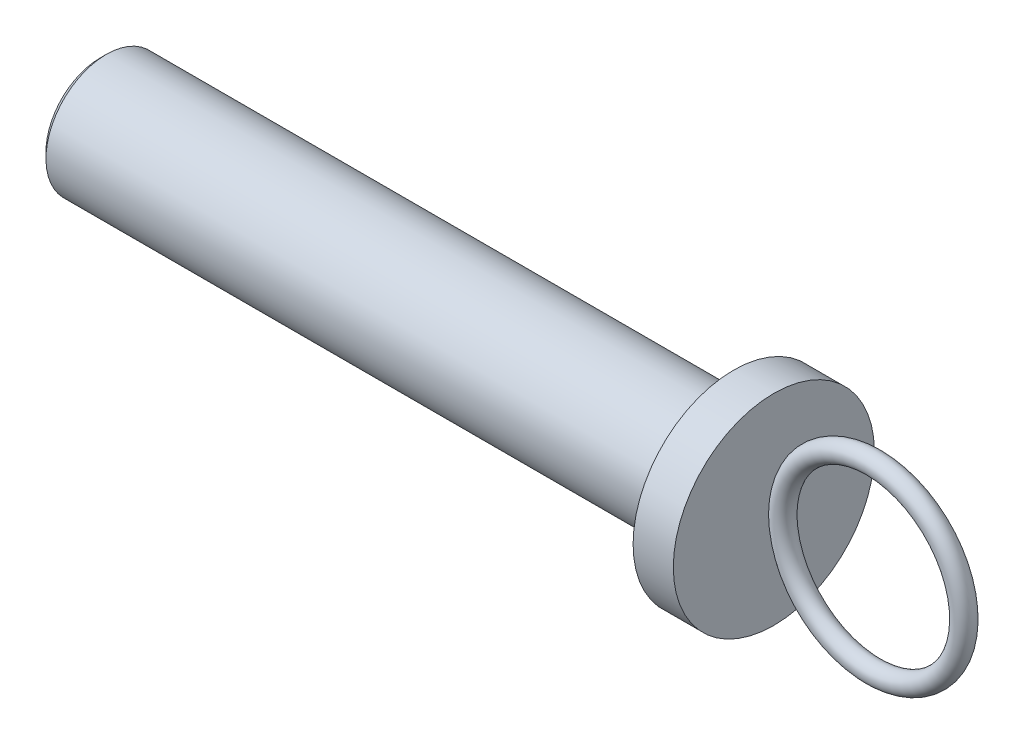
SolidWorks part; units mm, degrees
ref_plane "前视基准面" through (0, 0, 0) normal (0, 0, 1) x (1, 0, 0)
ref_plane "上视基准面" through (0, 0, 0) normal (0, 1, 0) x (1, 0, 0)
ref_plane "右视基准面" through (0, 0, 0) normal (1, 0, 0) x (0, 0, -1)
sketch "草图1" plane through (0, 0, 0) normal (0, 0, 1) x (1, 0, 0)
  line L0 (0, 0) -> (-335, 0)
  line L1 (0, 0) -> (0, 50)
  line L2 (0, 50) -> (-20, 50)
  line L3 (-20, 50) -> (-20, 30)
  line L4 (-20, 30) -> (-332, 30)
  line L5 (-332, 30) -> (-335, 27)
  line L6 (-335, 27) -> (-335, 0)
  dimension "D1" = 50
  dimension "D2" = 20
  dimension "D3" = 312
  dimension "D4" = 30
  dimension "D5" = 3
  dimension "D6" = 27
revolve "旋转1" add sketch "草图1" angle 360 about L0
sketch "草图2" plane through (0, 0, 0) normal (0, 1, 0) x (1, 0, 0)
  line L0 (-1000, 0) -> (49000, 0) construction
  line L2 (49.5, -1000) -> (49.5, 49000) construction
  line L3 (0, -50) -> (0, 50) construction
  circle A0 centre (4.5, 0) radius 5
  dimension "D1" = 10
  dimension "D2" = 45
  dimension "D3" = 4.5
revolve "旋转2" add sketch "草图2" angle 360 about L2
